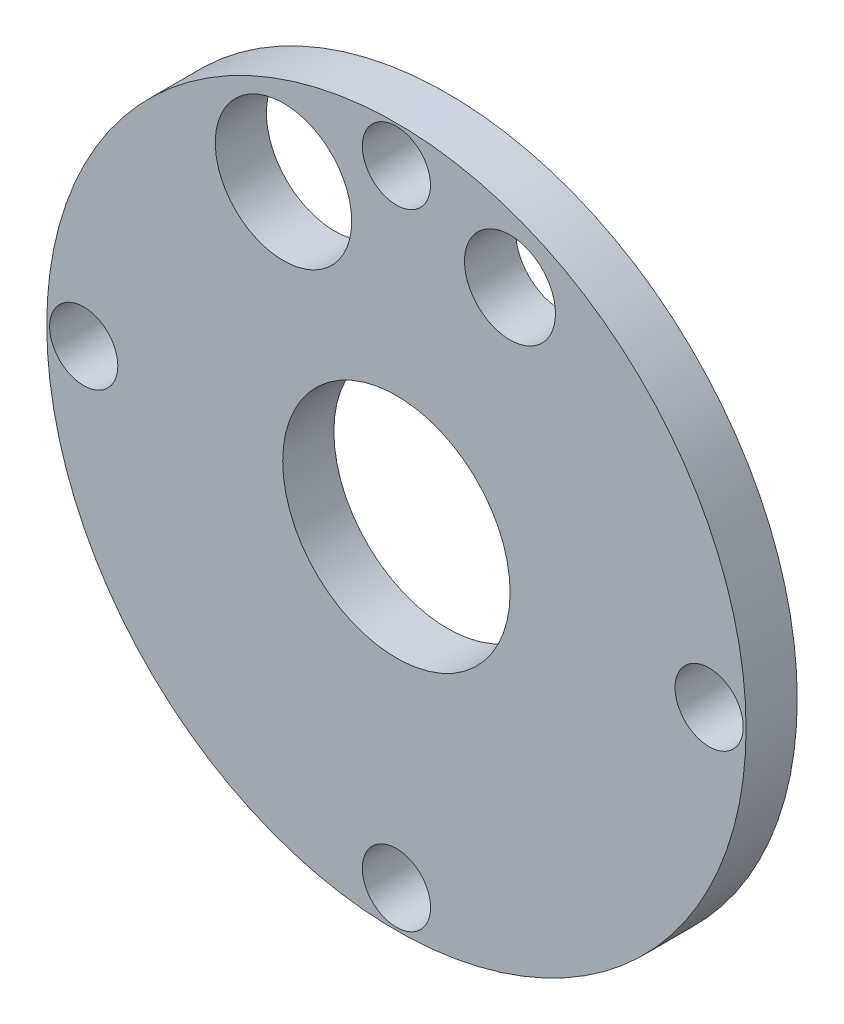
SolidWorks part; units mm, degrees
ref_plane "Plan de face" through (0, 0, 0) normal (0, 0, 1) x (1, 0, 0)
ref_plane "Plan de dessus" through (0, 0, 0) normal (0, 1, 0) x (1, 0, 0)
ref_plane "Plan de droite" through (0, 0, 0) normal (1, 0, 0) x (0, 0, -1)
sketch "Esquisse1" plane through (0, 0, 0) normal (0, 0, 1) x (1, 0, 0)
  circle A0 centre (0, 0) radius 30.75
  dimension "D1" = 61.5
extrude "Boss.-Extru.1" add sketch "Esquisse1" along normal blind 8
sketch "Esquisse2" plane through (0, 0, 8) normal (0, 0, 1) x (1, 0, 0)
  line L0 (-27.5, 0) -> (0, 0) construction
  line L1 (0, 0) -> (0, 27.5) construction
  line L2 (0, 0) -> (0, -27.5) construction
  circle A0 centre (0, 0) radius 27.5 construction
  circle A1 centre (0, 27.5) radius 3
  circle A2 centre (27.5, 0) radius 3
  circle A3 centre (-27.5, 0) radius 3
  circle A4 centre (0, -27.5) radius 3
  dimension "D2" = 55
  dimension "D3" = 6
  dimension "D1" = 90
extrude "Boss.-Extru.2" add sketch "Esquisse2" along normal blind 56
sketch "Esquisse4" plane through (0, 0, 64) normal (0, 0, 1) x (1, 0, 0)
  circle A0 centre (0, 0) radius 30.75
  dimension "D1" = 61.5
extrude "Boss.-Extru.4" add sketch "Esquisse4" along normal blind 4.5
sketch "Esquisse6" plane through (0, 0, 68.5) normal (0, 0, 1) x (1, 0, 0)
  circle A7 centre (0, -27.5) radius 3 construction
  circle A8 centre (-27.5, 0) radius 3 construction
  circle A9 centre (0, 27.5) radius 3 construction
  circle A10 centre (27.5, 0) radius 3 construction
  circle A11 centre (0, -27.5) radius 3
  circle A12 centre (-27.5, 0) radius 3
  circle A13 centre (0, 27.5) radius 3
  circle A14 centre (27.5, 0) radius 3
extrude "Boss.-Extru.5" add sketch "Esquisse6" along normal blind 40
sketch "Esquisse12" plane through (0, 0, 68.5) normal (0, 0, 1) x (1, 0, 0)
  circle A0 centre (9.9869, 23.2244) radius 4
  dimension "D1" = 8
extrude "Enlèv. mat.-Extru.1" cut sketch "Esquisse12" against normal blind 6
sketch "Esquisse13" plane through (0, 0, 68.5) normal (0, 0, 1) x (1, 0, 0)
  line L0 (0, 23.5) -> (0, 0) construction
  line L1 (0, 0) -> (-9.9315, 21.2982) construction
  circle A0 centre (-9.9315, 21.2982) radius 6
  circle A1 centre (0, 0) radius 23.5 construction
  point P1 (-14.8464, 24.9336)
  dimension "D1" = 47
  dimension "D3" = 12
  dimension "D2" = 25
extrude "Enlèv. mat.-Extru.2" cut sketch "Esquisse13" against normal blind 10
sketch "Esquisse15" plane through (0, 0, 68.5) normal (0, 0, 1) x (1, 0, 0)
  circle A0 centre (0, 0) radius 10
  dimension "D1" = 20
extrude "Enlèv. mat.-Extru.3" cut sketch "Esquisse15" against normal blind 10 contours A0
sketch "Esquisse18" plane through (0, 0, 108.5) normal (0, 0, 1) x (1, 0, 0)
  circle A1 centre (0, 0) radius 30.75
  circle A2 centre (0, 0) radius 30.75
  dimension "D1" = 0
extrude "Boss.-Extru.10" add sketch "Esquisse18" along normal blind 4.5
ref_plane "Plan1" through (-30.75, 0, 0) normal (-1, 0, 0) x (0, 0, 1)
sketch "Esquisse19" plane through (-30.75, 0, 0) normal (-1, 0, 0) x (0, 0, 1)
  line L0 (0, 30.75) -> (0, -30.75) construction
  line L1 (0, -30.75) -> (8, -30.75) construction
  circle A0 centre (4, 0.25) radius 2.05
  dimension "D1" = 4.1
  dimension "D2" = 4
  dimension "D3" = 31
extrude "Enlèv. mat.-Extru.4" cut sketch "Esquisse19" against normal blind 62
sketch "Esquisse20" plane through (0, 0, 113) normal (0, 0, 1) x (1, 0, 0)
  line L0 (0, 0) -> (-14.913, 21.298) construction
  line L1 (0, 0) -> (21.298, 14.913) construction
  line L2 (0, 0) -> (0, 14.8545) construction
  circle A0 centre (0, 0) radius 30.75 construction
  circle A1 centre (21.298, 14.913) radius 3.5
  circle A2 centre (-14.913, 21.298) radius 3.5
  circle A3 centre (-21.298, -14.913) radius 3.5
  circle A4 centre (14.913, -21.298) radius 3.5
  dimension "D2" = 7
  dimension "D1" = 26
  dimension "D3" = 90
  dimension "D4" = 35
extrude "Enlèv. mat.-Extru.5" cut sketch "Esquisse20" against normal blind 10
sketch "Esquisse21" plane through (0, 0, 64) normal (0, 0, -1) x (-1, 0, 0)
  circle A0 centre (0, 27.5) radius 3 construction
  circle A1 centre (-27.5, 0) radius 3 construction
  circle A2 centre (0, -27.5) radius 3 construction
  circle A3 centre (27.5, 0) radius 3 construction
  circle A4 centre (0, 27.5) radius 3
  circle A5 centre (-27.5, 0) radius 3
  circle A6 centre (0, -27.5) radius 3
  circle A7 centre (27.5, 0) radius 3
extrude "Enlèv. mat.-Extru.6" cut sketch "Esquisse21" against normal through all
sketch "Esquisse22" plane through (0, 0, 0) normal (0, 1, 0) x (1, 0, 0)
  line L0 (30.75, -1.9653) -> (30.75, 0) construction
  line L1 (-30.75, -64) -> (30.75, -64)
  line L2 (-30.75, -64) -> (-30.75, 0)
  line L3 (-30.75, 0) -> (30.75, 0)
  line L4 (30.75, -64) -> (30.75, 0)
  line L7 (-30.75, -113) -> (30.75, -113)
  line L8 (-30.75, -113) -> (-30.75, -108.5)
  line L9 (-30.75, -108.5) -> (30.75, -108.5)
  line L10 (30.75, -113) -> (30.75, -108.5)
extrude "Enlèv. mat.-Extru.7" cut sketch "Esquisse22" against normal through all and the other way through all
